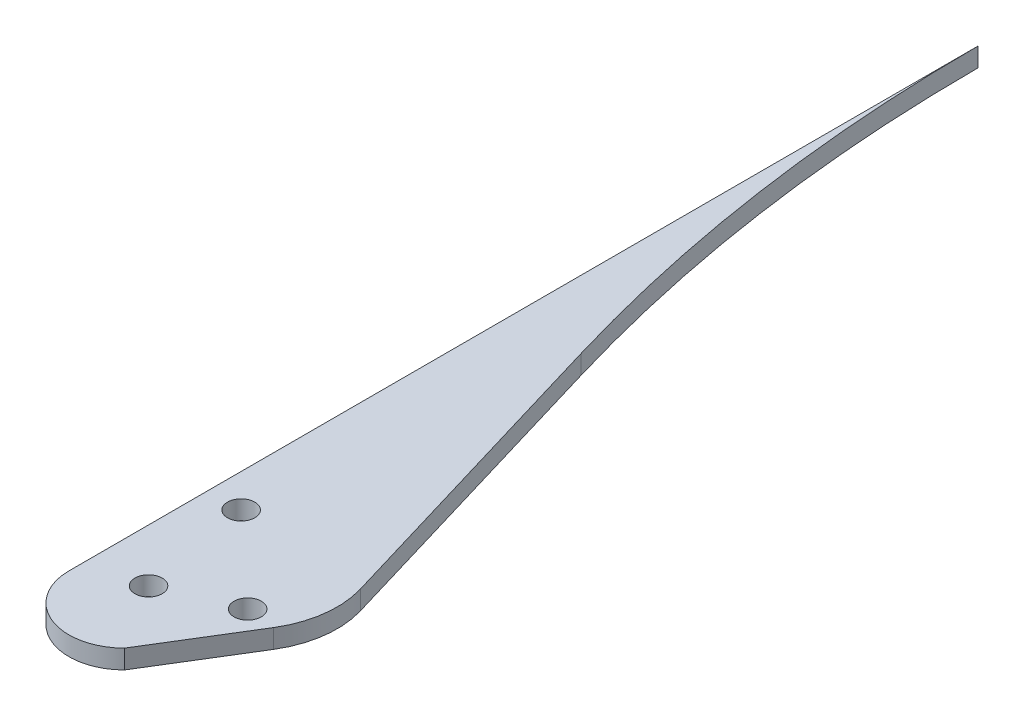
SolidWorks part; units mm, degrees
material "Acrylic (Medium-high impact)"
ref_plane "Front Plane" through (0, 0, 0) normal (0, 0, 1) x (1, 0, 0)
ref_plane "Top Plane" through (0, 0, 0) normal (0, 1, 0) x (1, 0, 0)
ref_plane "Right Plane" through (0, 0, 0) normal (1, 0, 0) x (0, 0, -1)
sketch "Sketch1" plane through (0, 0, 0) normal (0, 1, 0) x (1, 0, 0)
  line L12 (0, 304.8) -> (0, 0) construction
  line L23 (31.75, -13.0735) -> (50.7652, 17.8819)
  line L24 (54.1393, 43.5679) -> (22.7226, 148.99)
  line L27 (0, 0) -> (31.75, -13.0735) construction
  line L28 (-19.05, 114.3) -> (0, 114.3)
  line L29 (0, 304.8) -> (-19.05, 304.8)
  line L30 (0, 114.3) -> (0, 0)
  line L32 (-19.05, 304.8) -> (-19.05, 114.3)
  arc A14 (0, 0) -> (31.75, -13.0735) centre (18.5666, 0) ccw
  arc A15 (50.7652, 17.8819) -> (54.1393, 43.5679) centre (23.7117, 34.5003) ccw
  arc A16 (22.7226, 148.99) -> (0, 304.8) centre (545.5597, 304.8) cw
other "AlignGroup1" parameters "D5"=10.6777, "D2"=6.35, "D11"=87.1705, "D12"=33.4582, "D8"=31.75, "D9"=9.7381, "D13"=69.443, "D14"=18.5666, "D15"=145.5834, "D1"=112.3753, "D3"=95.7306, "D4"=21.8056, "D6"=224.7252, "D7"=76.8916, "D10"=53.7406
extrude "Boss-Extrude1" add sketch "Sketch1" along normal blind 6.35
ref_plane "Plane1" through (0, 0, 18.5666) normal (0, 0, 1) x (1, 0, 0)
sketch "Sketch2" plane through (0, 6.35, 0) normal (0, 1, 0) x (1, 0, 0)
  line L1 (0, 114.3) -> (-19.05, 114.3)
  line L2 (0, 114.3) -> (0, 304.8)
  line L3 (0, 304.8) -> (-19.05, 304.8)
  line L4 (-19.05, 114.3) -> (-19.05, 304.8)
extrude "Cut-Extrude1" cut sketch "Sketch2" against normal through all
sketch "Sketch3" plane through (0, 6.35, 0) normal (0, 1, 0) x (1, 0, 0)
  circle A0 centre (11.1782, 46.5763) radius 4.572 construction
  circle A1 centre (36.5782, 46.5709) radius 4.572 construction
  circle A2 centre (11.1782, 46.5763) radius 4.572
  circle A3 centre (36.5782, 46.5709) radius 4.572 construction
  circle A4 centre (17.7079, 9.006) radius 4.572 construction
  circle A5 centre (41.038, 18.9005) radius 4.572 construction
  circle A6 centre (17.7079, 9.006) radius 4.572
  circle A7 centre (41.038, 18.9005) radius 4.572
extrude "Cut-Extrude2" cut sketch "Sketch3" against normal through all
